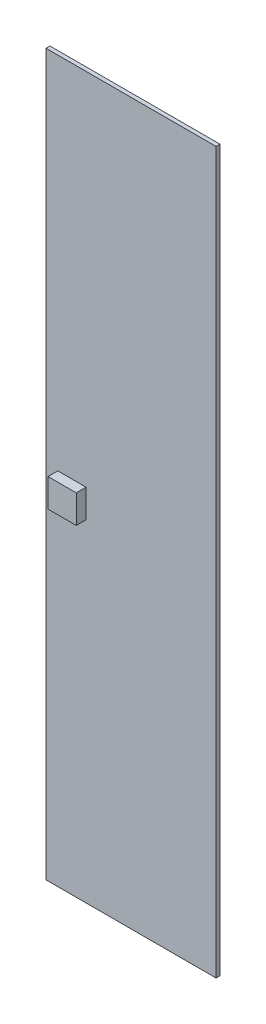
SolidWorks part; units mm, degrees
ref_plane "Plan de face" through (0, 0, 0) normal (0, 0, 1) x (1, 0, 0)
ref_plane "Plan de dessus" through (0, 0, 0) normal (0, 1, 0) x (1, 0, 0)
ref_plane "Plan de droite" through (0, 0, 0) normal (1, 0, 0) x (0, 0, -1)
sketch "Esquisse1" plane through (0, 0, 0) normal (0, 0, 1) x (1, 0, 0)
  line L1 (-216.75, -918.5) -> (216.75, -918.5)
  line L2 (-216.75, -918.5) -> (-216.75, 918.5)
  line L3 (-216.75, 918.5) -> (216.75, 918.5)
  line L4 (216.75, -918.5) -> (216.75, 918.5)
  line L5 (-216.75, -918.5) -> (216.75, 918.5) construction
  line L6 (-216.75, 918.5) -> (216.75, -918.5) construction
  point P0 (0, 0)
  dimension "D1" = 433.5
  dimension "D2" = 1837
extrude "Boss.-Extru.1" add sketch "Esquisse1" along normal blind 10
sketch "Esquisse2" plane through (0, 0, 10) normal (0, 0, 1) x (1, 0, 0)
  line L1 (-186.75, -72) -> (-114.75, -72)
  line L2 (-186.75, -72) -> (-186.75, 0)
  line L3 (-186.75, 0) -> (-114.75, 0)
  line L4 (-114.75, -72) -> (-114.75, 0)
  line L5 (-186.75, -72) -> (-114.75, 0) construction
  line L6 (-186.75, 0) -> (-114.75, -72) construction
  point P0 (-150.75, -36)
  dimension "D1" = 72
  dimension "D2" = 72
  dimension "D3" = 846.5
  dimension "D4" = 30
extrude "Boss.-Extru.2" add sketch "Esquisse2" along normal blind 25 and the other way blind 40
